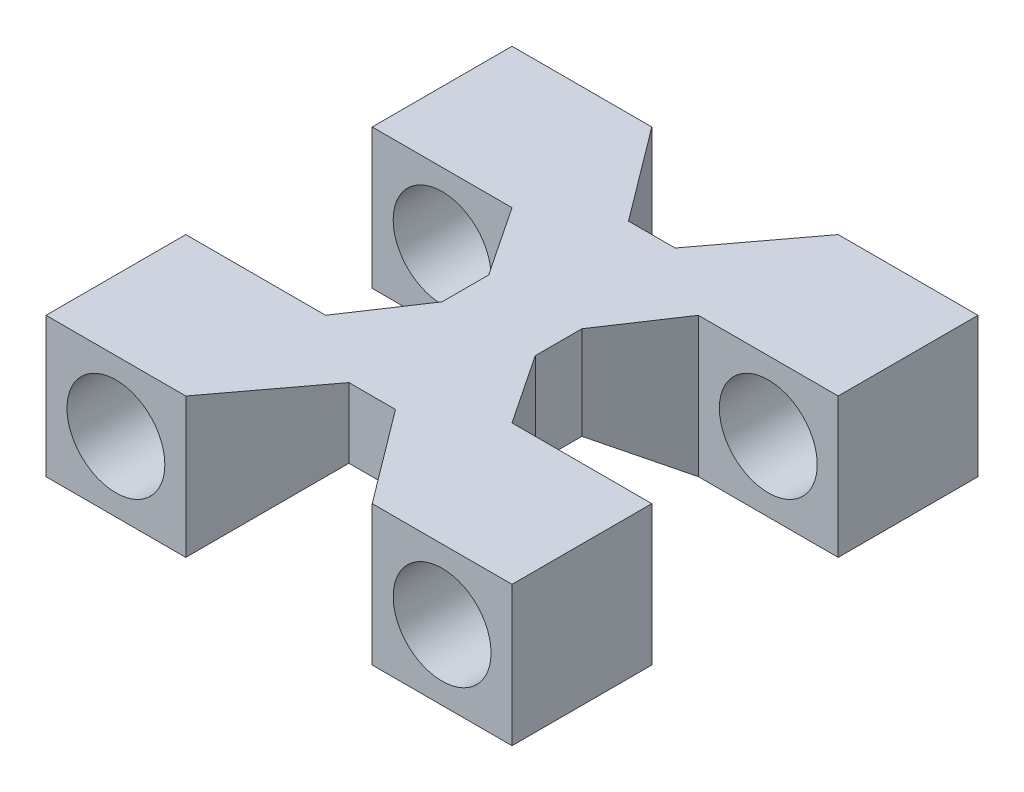
SolidWorks part; units mm, degrees
ref_plane "Спереди" through (0, 0, 0) normal (0, 0, 1) x (1, 0, 0)
ref_plane "Сверху" through (0, 0, 0) normal (0, 1, 0) x (1, 0, 0)
ref_plane "Справа" through (0, 0, 0) normal (1, 0, 0) x (0, 0, -1)
sketch "Эскиз2" plane through (0, 0, 0) normal (0, 1, 0) x (1, 0, 0)
  line L0 (-20, 50) -> (-50, 50)
  line L1 (-50, 50) -> (-50, 20)
  line L2 (20, 50) -> (50, 50)
  line L3 (50, 50) -> (50, 20)
  line L4 (-50, -20) -> (-50, -50)
  line L5 (-50, -50) -> (-20, -50)
  line L6 (50, -50) -> (50, -20)
  line L7 (50, -50) -> (20, -50)
  line L8 (-50, 20) -> (-20, 20)
  line L9 (50, 20) -> (20, 20)
  line L10 (50, -20) -> (20, -20)
  line L11 (-50, -20) -> (-20, -20)
  line L12 (0, 94.35) -> (0, -119.85) construction
  line L13 (-123, 0) -> (122.1, 0) construction
  line L14 (-5, 30) -> (5, 30)
  line L15 (10, 5) -> (10, -5)
  line L16 (-10, 5) -> (-10, -5)
  line L17 (-5, -30) -> (5, -30)
  line L18 (-20, 50) -> (-5, 30)
  line L19 (5, 30) -> (20, 50)
  line L20 (-20, 20) -> (-10, 5)
  line L21 (-20, -20) -> (-10, -5)
  line L22 (-20, -50) -> (-5, -30)
  line L23 (5, -30) -> (20, -50)
  line L24 (10, -5) -> (20, -20)
  line L25 (10, 5) -> (20, 20)
  point P29 (0, -30)
  point P30 (-10, 0)
  point P31 (10, 0)
  point P32 (0, 30)
  dimension "D1" = 30
  dimension "D2" = 30
  dimension "D3" = 50
  dimension "D4" = 50
  dimension "D5" = 50
  dimension "D6" = 50
  dimension "D7" = 10
  dimension "D8" = 50
  dimension "D9" = 50
  dimension "D10" = 50
  dimension "D11" = 50
  dimension "D12" = 10
  dimension "D13" = 30
  dimension "D14" = 30
  dimension "D15" = 10
  dimension "D16" = 10
extrude "Бобышка-Вытянуть2" add sketch "Эскиз2" along normal blind 30
sketch "Эскиз3" plane through (0, 0, 50) normal (0, 0, 1) x (1, 0, 0)
  line L0 (-50, 30) -> (-20, 30) construction
  line L1 (-50, 30) -> (-50, 0) construction
  circle A0 centre (-35, 15) radius 10.5
  dimension "D3" = 21
  dimension "D1" = 15
  dimension "D2" = 15
extrude "Вырез-Вытянуть1" cut sketch "Эскиз3" against normal up to surface (30 mm away) up to face at (-35, 15, 20)
sketch "Эскиз4" plane through (0, 0, -50) normal (0, 0, -1) x (-1, 0, 0)
  line L0 (20, 30) -> (50, 30) construction
  line L1 (50, 30) -> (50, 0) construction
  circle A0 centre (35, 15) radius 10.5
  point P6 (50, 15)
  dimension "D3" = 21
  dimension "D1" = 15
  dimension "D2" = 15
extrude "Вырез-Вытянуть2" cut sketch "Эскиз4" against normal up to surface (30 mm away) up to face at (-35, 15, -20)
sketch "Эскиз5" plane through (0, 0, -50) normal (0, 0, -1) x (-1, 0, 0)
  line L0 (-50, 30) -> (-20, 30) construction
  line L1 (-50, 30) -> (-50, 0) construction
  circle A0 centre (-35, 15) radius 10.5
  dimension "D3" = 21
  dimension "D1" = 15
  dimension "D2" = 15
extrude "Вырез-Вытянуть3" cut sketch "Эскиз5" against normal up to surface (30 mm away) up to face at (35, 15, -20)
sketch "Эскиз6" plane through (0, 0, 50) normal (0, 0, 1) x (1, 0, 0)
  line L0 (20, 30) -> (50, 30) construction
  line L1 (50, 30) -> (50, 0) construction
  circle A0 centre (35, 15) radius 10.5
  dimension "D3" = 21
  dimension "D1" = 15
  dimension "D2" = 15
extrude "Вырез-Вытянуть4" cut sketch "Эскиз6" against normal up to surface (30 mm away) up to face at (35, 15, 20)
sketch "Эскиз7" plane through (0, 0, 30) normal (0, 0, 1) x (1, 0, 0)
  line L0 (-20, 0) -> (-5, 15)
  line L1 (-5, 30) -> (-5, 0) construction
  line L2 (-5, 15) -> (5, 15)
  line L3 (5, 30) -> (5, 0) construction
  line L4 (5, 15) -> (20, 0)
  line L5 (20, 0) -> (-20, 0)
extrude "Вырез-Вытянуть5" cut sketch "Эскиз7" against normal through all both and the other way through all
